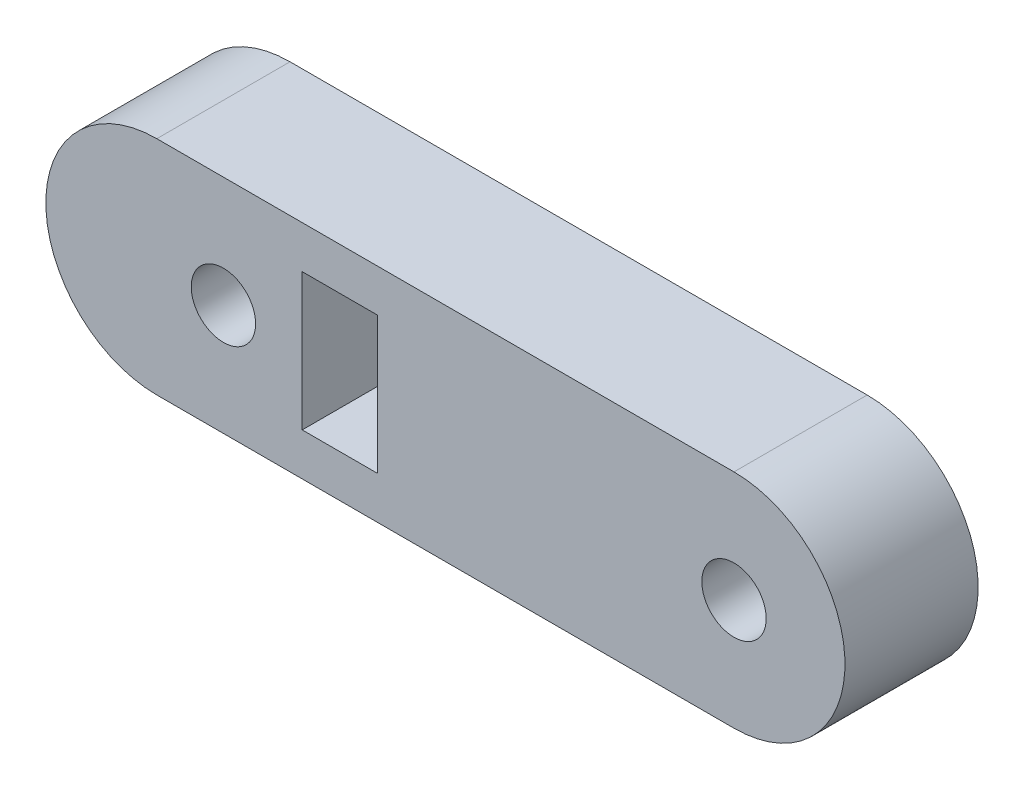
SolidWorks part; units mm, degrees
ref_plane "Front Plane" through (0, 0, 0) normal (0, 0, 1) x (1, 0, 0)
ref_plane "Top Plane" through (0, 0, 0) normal (0, 1, 0) x (1, 0, 0)
ref_plane "Right Plane" through (0, 0, 0) normal (1, 0, 0) x (0, 0, -1)
sketch "Sketch1" plane through (0, 0, 0) normal (0, 0, 1) x (1, 0, 0)
  line L0 (595.0214, 463.5696) -> (595.0214, 460.4829) construction
  line L1 (595.0214, 460.4829) -> (595.0214, 457.3962) construction
  line L2 (596.7214, 463.5696) -> (596.7214, 457.3962)
  line L3 (596.7214, 457.3962) -> (593.3214, 457.3962)
  line L4 (593.3214, 457.3962) -> (593.3214, 463.5696)
  line L5 (593.3214, 463.5696) -> (596.7214, 463.5696)
  line L6 (595.0214, 463.5696) -> (595.0214, 465.4829) construction
  line L7 (589.7714, 460.4829) -> (589.7714, 465.4829) construction
  line L8 (589.7714, 460.4829) -> (589.7714, 455.4829) construction
  line L9 (612.7714, 460.4829) -> (612.7714, 465.4829) construction
  line L10 (612.7714, 460.4829) -> (612.7714, 455.4829) construction
  line L11 (589.7714, 465.4829) -> (612.7714, 465.4829)
  line L12 (589.7714, 455.4829) -> (612.7714, 455.4829)
  line L13 (593.3214, 460.4829) -> (595.0214, 460.4829) construction
  line L14 (595.0214, 460.4829) -> (596.7214, 460.4829) construction
  line L15 (589.7714, 460.4829) -> (595.0214, 460.4829) construction
  line L16 (612.7714, 460.4829) -> (595.0214, 460.4829) construction
  line L17 (595.0214, 460.4829) -> (589.7714, 460.4829) construction
  line L18 (589.7714, 465.4829) -> (586.7714, 465.4829)
  line L19 (589.7714, 455.4829) -> (586.7714, 455.4829)
  circle A0 centre (589.7714, 460.4829) radius 1.45
  circle A1 centre (612.7714, 460.4829) radius 1.45
  arc A2 (586.7714, 465.4829) -> (586.7714, 455.4829) centre (586.7714, 460.4829) ccw
  arc A3 (612.7714, 455.4829) -> (612.7714, 465.4829) centre (612.7714, 460.4829) ccw
  point P19 (591.2214, 460.4829)
  dimension "D1" = 2.1
  dimension "D2" = 2.9
  dimension "D3" = 23
extrude "Boss-Extrude1" add sketch "Sketch1" along normal blind 6
